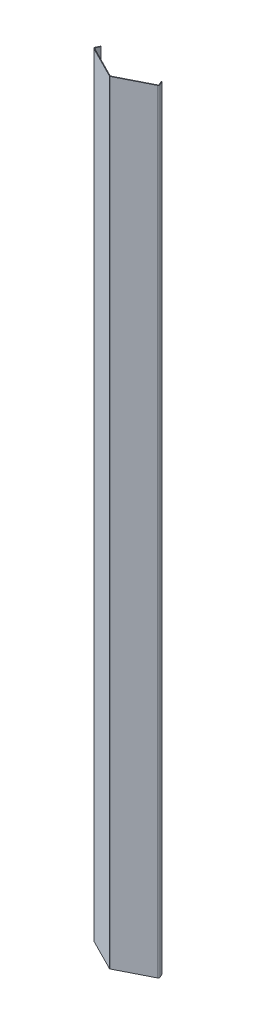
SolidWorks part; units mm, degrees
material "ASTM A36 Steel"
ref_plane "Front Plane" through (0, 0, 0) normal (0, 0, 1) x (1, 0, 0)
ref_plane "Top Plane" through (0, 0, 0) normal (0, 1, 0) x (1, 0, 0)
ref_plane "Right Plane" through (0, 0, 0) normal (1, 0, 0) x (0, 0, -1)
sketch "Sketch1" plane through (0, 0, 0) normal (0, 1, 0) x (1, 0, 0)
  line L3 (319.2222, 134.9653) -> (331.4949, 107.6505)
  line L5 (112.7099, -13.8833) -> (326.8928, 94.6317)
  line L15 (-99.1928, 133.3259) -> (-111.4654, 106.0111)
  line L16 (105.4787, -10.3152) -> (-108.7041, 98.1998)
  line L17 (110.9021, -10.3152) -> (325.085, 98.1998)
  line L18 (315.5736, 133.3259) -> (327.8462, 106.0111)
  line L20 (103.6709, -13.8833) -> (-110.5119, 94.6317)
  line L21 (-102.8414, 134.9653) -> (-115.114, 107.6505)
  line L22 (-102.8414, 134.9653) -> (-99.1928, 133.3259)
  line L23 (319.2222, 134.9653) -> (315.5736, 133.3259)
  arc A0 (331.4949, 107.6505) -> (326.8928, 94.6317) centre (322.3733, 103.5521) cw
  arc A2 (103.6709, -13.8833) -> (112.7099, -13.8833) centre (108.1904, -4.9629) ccw
  arc A6 (-111.4654, 106.0111) -> (-108.7041, 98.1998) centre (-105.9924, 103.5521) ccw
  arc A7 (105.4787, -10.3152) -> (110.9021, -10.3152) centre (108.1904, -4.9629) ccw
  arc A8 (327.8462, 106.0111) -> (325.085, 98.1998) centre (322.3733, 103.5521) cw
  arc A11 (-115.114, 107.6505) -> (-110.5119, 94.6317) centre (-105.9924, 103.5521) ccw
  point P7 (335.4063, 98.945)
  point P31 (-119.0254, 98.945)
  dimension "D2" = 10
  dimension "D1" = 4
extrude "Boss-Extrude2" add sketch "Sketch1" along normal blind 5330
